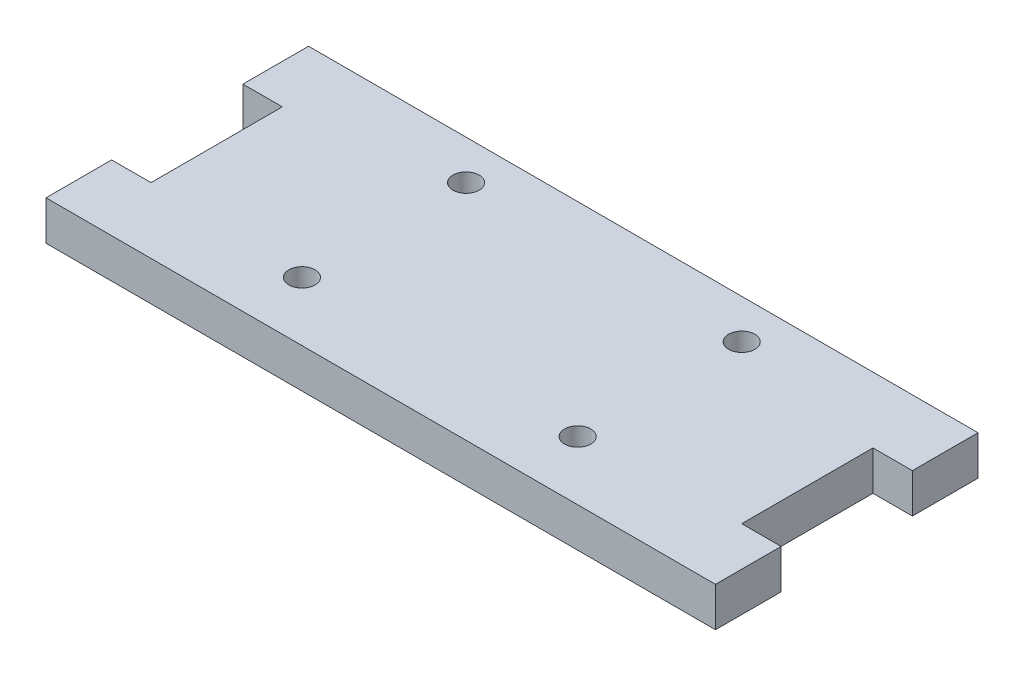
SolidWorks part; units mm, degrees
ref_plane "Front Plane" through (0, 0, 0) normal (0, 0, 1) x (1, 0, 0)
ref_plane "Top Plane" through (0, 0, 0) normal (0, 1, 0) x (1, 0, 0)
ref_plane "Right Plane" through (0, 0, 0) normal (1, 0, 0) x (0, 0, -1)
sketch "Sketch1" plane through (0, 0, 0) normal (0, 1, 0) x (1, 0, 0)
  line L0 (22.5, 20) -> (22.5, 0)
  line L1 (0, 0) -> (45, 0)
  line L2 (0, 0) -> (0, 20)
  line L3 (0, 20) -> (45, 20)
  line L4 (45, 0) -> (45, 20)
  line L5 (45, 15) -> (48, 15)
  line L6 (0, 20) -> (-3, 20)
  line L7 (0, 20) -> (0, 15)
  line L8 (0, 15) -> (-3, 15)
  line L9 (-3, 20) -> (-3, 15)
  line L10 (48, 20) -> (48, 15)
  line L11 (45, 20) -> (48, 20)
  line L12 (45, 0) -> (48, 0)
  line L13 (0, 0) -> (-3, 0)
  line L14 (0, 0) -> (0, 5)
  line L15 (0, 5) -> (-3, 5)
  line L16 (-3, 0) -> (-3, 5)
  line L17 (48, 0) -> (48, 5)
  line L18 (45, 5) -> (48, 5)
  circle A0 centre (12, 17) radius 1
  circle A1 centre (12, 4.5) radius 1
  circle A2 centre (33, 4.5) radius 1
  circle A3 centre (33, 17) radius 1
  dimension "D3" = 2
  dimension "D5" = 2
  dimension "D1" = 45
  dimension "D2" = 20
  dimension "D4" = 10.5
  dimension "D6" = 12.5
  dimension "D7" = 3
  dimension "D8" = 3
  dimension "D9" = 5
  dimension "D10" = 5
  dimension "D11" = 3
extrude "Boss-Extrude1" add sketch "Sketch1" along normal blind 3 contours L6 L9 L8 L2 | L3 L2 L1 L0 A1 A0 | L1 L4 L3 L0 A2 A3 | L11 L4 L5 L10 | L16 L13 L2 L15 | L18 L4 L12 L17
